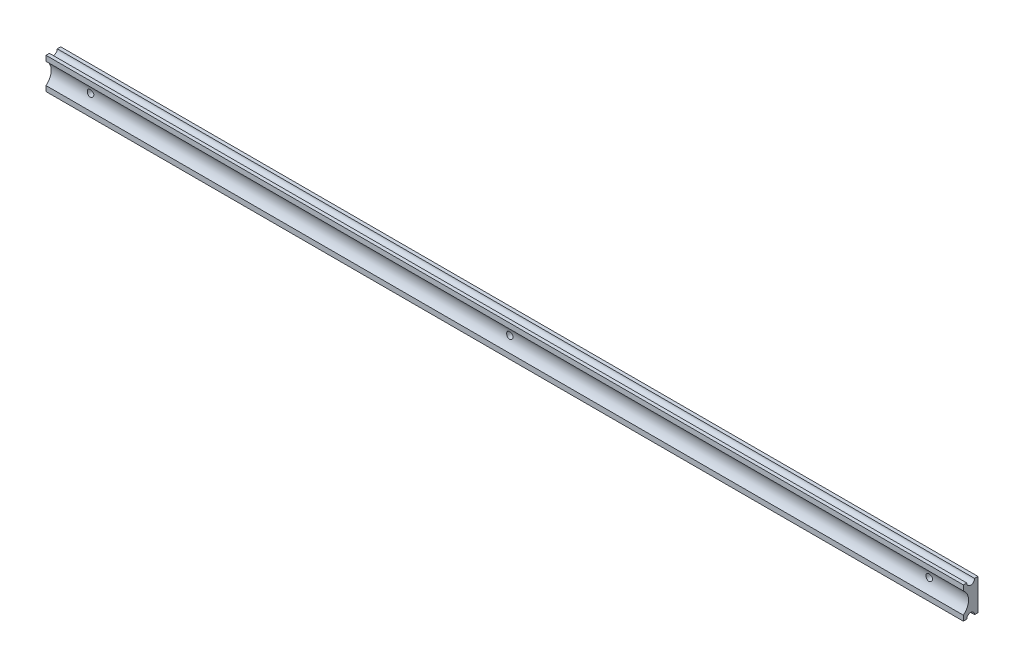
SolidWorks part; units mm, degrees
material "6061 合金"
ref_plane "前视基准面" through (0, 0, 0) normal (0, 0, 1) x (1, 0, 0)
ref_plane "上视基准面" through (0, 0, 0) normal (0, 1, 0) x (1, 0, 0)
ref_plane "右视基准面" through (0, 0, 0) normal (1, 0, 0) x (0, 0, -1)
sketch "草图1" plane through (0, 0, 0) normal (1, 0, 0) x (0, 0, -1)
  line L0 (0, -6) -> (0, 6)
  line L1 (0, 6) -> (5.6, 6)
  line L2 (5.6, 6) -> (5.6, -6)
  line L3 (5.6, -6) -> (0, -6)
  point P4 (0, 0)
  dimension "D1" = 12
  dimension "D2" = 5.6
extrude "凸台-拉伸1" add sketch "草图1" along normal mid plane 350
sketch "草图2" plane through (175, 0, 0) normal (1, 0, 0) x (0, 0, -1)
  line L0 (5.6, 6) -> (0, 6) construction
  line L1 (0, -6) -> (5.6, -6) construction
  circle A0 centre (2.8, 6) radius 1.5
  circle A1 centre (2.8, -6) radius 1.5
  dimension "D1" = 3
extrude "切除-拉伸1" cut sketch "草图2" against normal blind 350
sketch "草图3" plane through (175, 0, 0) normal (1, 0, 0) x (0, 0, -1)
  line L0 (-3, 0) -> (0, 0) construction
  line L1 (0, 6) -> (0, -6) construction
  circle A0 centre (-3, 0) radius 5
  dimension "D1" = 10
  dimension "D2" = 3
extrude "切除-拉伸2" cut sketch "草图3" against normal blind 350
sketch "草图4" plane through (0, 0, -5.6) normal (0, 0, -1) x (-1, 0, 0)
  line L0 (-175, 0) -> (-160, 0) construction
  line L1 (-175, -6) -> (-175, 6) construction
  dimension "D1" = 15
hole_wizard "M3 螺纹孔1" positions "草图5" profile "草图6" tap size "M3" standard "GB" end condition through all
sketch "草图5" plane through (0, 0, -5.6) normal (0, 0, -1) x (-1, 0, 0)
  point P0 (-160, 0)
sketch "草图6" plane through (160, 0, -5.6) normal (1, 0, 0) x (0, 1, 0)
  line L0 (0, 0) -> (0, 5.6)
  line L1 (0, 5.6) -> (1.25, 5.6)
  line L2 (1.25, 5.6) -> (1.25, 0)
  line L5 (1.25, 0) -> (0, 0)
  line L11 (0, -6.35) -> (0, 107.95) construction
  dimension "通孔螺纹孔钻头直径" = 2.5
  dimension "通孔螺纹孔钻头深度" = 5.6
cosmetic thread "孔螺蚊线1" parameters "D2"=3
pattern_linear "阵列(线性)2" count 3 spacing 160 along (-1, 0, 0) of "M3 螺纹孔1"
cosmetic thread "孔螺蚊线2" parameters "D2"=3
cosmetic thread "孔螺蚊线3" parameters "D2"=3
sketch "草图8" plane through (0, 6, 0) normal (0, 1, 0) x (1, 0, 0)
  line L0 (0, 0) -> (0, 5.6)
  line L1 (175, 0) -> (-175, 0) construction
  line L2 (175, 5.6) -> (-175, 5.6) construction
surface "曲面-拉伸1" sketch "草图8" parameters "D1"=10
